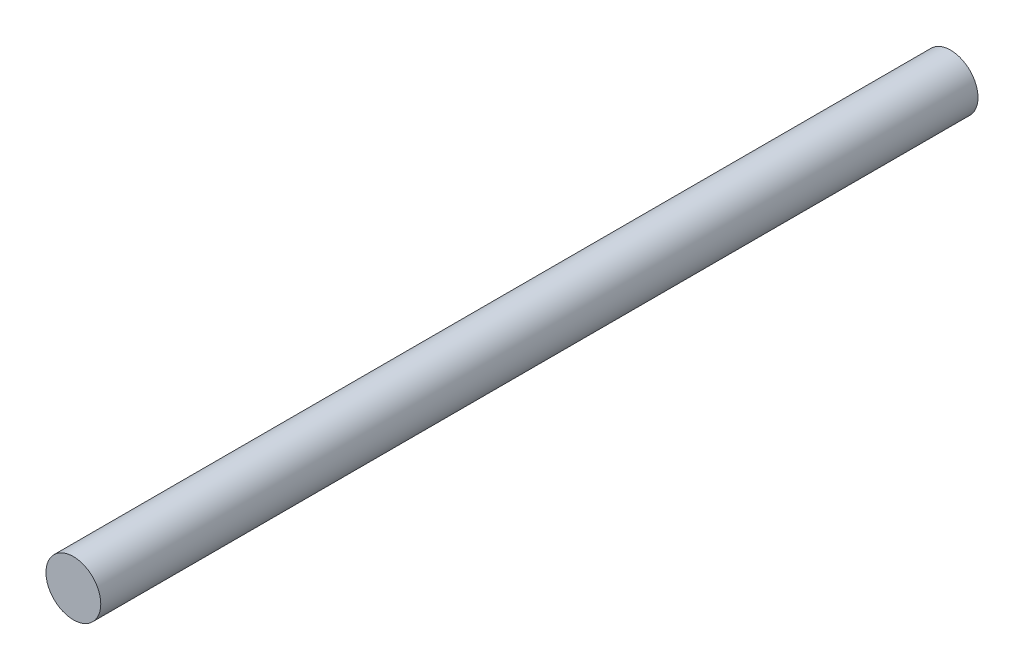
SolidWorks part; units mm, degrees
material "Plain Carbon Steel"
ref_plane "Front" through (0, 0, 0) normal (0, 0, 1) x (1, 0, 0)
ref_plane "Top" through (0, 0, 0) normal (0, 1, 0) x (1, 0, 0)
ref_plane "Right" through (0, 0, 0) normal (1, 0, 0) x (0, 0, -1)
sketch "Sketch1" plane through (0, 0, 0) normal (0, 0, 1) x (1, 0, 0)
  circle A0 centre (0, 0) radius 1.5875
  dimension "D1" = 3.175
extrude "Base Extrude" add sketch "Sketch1" along normal mid plane 50.8
